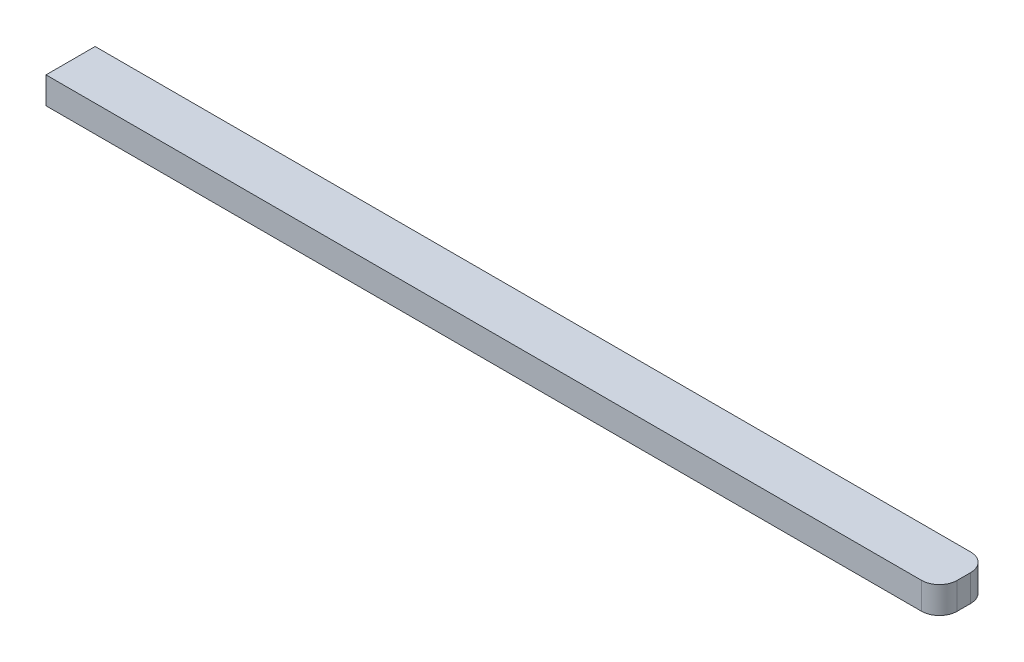
SolidWorks part; units mm, degrees
ref_plane "Спереди" through (0, 0, 0) normal (0, 0, 1) x (1, 0, 0)
ref_plane "Сверху" through (0, 0, 0) normal (0, 1, 0) x (1, 0, 0)
ref_plane "Справа" through (0, 0, 0) normal (1, 0, 0) x (0, 0, -1)
sketch "Эскиз1" plane through (0, 0, 0) normal (0, 1, 0) x (1, 0, 0)
  line L1 (-56.5967, 1.8813) -> (43.4033, 1.8813)
  line L2 (-56.5967, 1.8813) -> (-56.5967, -3.6187)
  line L3 (-56.5967, -3.6187) -> (43.4033, -3.6187)
  line L4 (43.4033, 1.8813) -> (43.4033, -3.6187)
  dimension "D1" = 5.5
  dimension "D2" = 100
extrude "Бобышка-Вытянуть1" add sketch "Эскиз1" along normal blind 3
fillet "Скругление1" radius 2 2 edges at (43.4033, 1.5, -1.8813) (43.4033, 1.5, 3.6187)
